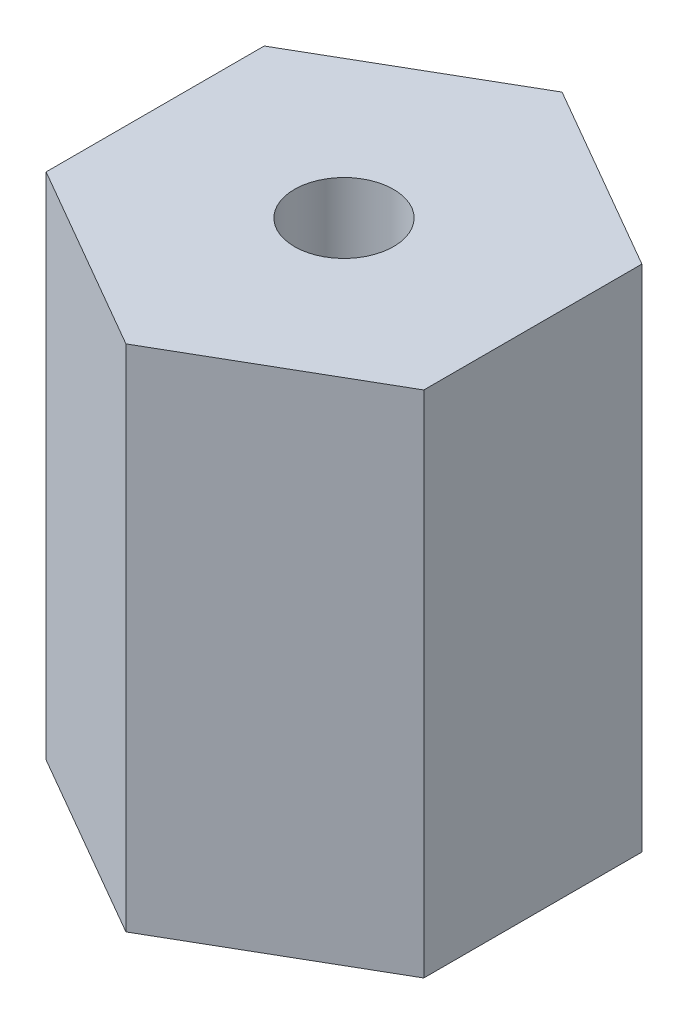
SolidWorks part; units mm, degrees
material "6061-T6 (SS)"
ref_plane "Front Plane" through (0, 0, 0) normal (0, 0, 1) x (1, 0, 0)
ref_plane "Top Plane" through (0, 0, 0) normal (0, 1, 0) x (1, 0, 0)
ref_plane "Right Plane" through (0, 0, 0) normal (1, 0, 0) x (0, 0, -1)
sketch "Sketch1" plane through (0, 0, 0) normal (0, 1, 0) x (1, 0, 0)
  line L1 (2.2606, 1.3052) -> (0, 2.6103)
  line L2 (0, 2.6103) -> (-2.2606, 1.3052)
  line L3 (-2.2606, 1.3052) -> (-2.2606, -1.3052)
  line L4 (-2.2606, -1.3052) -> (0, -2.6103)
  line L5 (0, -2.6103) -> (2.2606, -1.3052)
  line L6 (2.2606, -1.3052) -> (2.2606, 1.3052)
  circle A0 centre (0, 0) radius 2.2606 construction
  dimension "D1" = 4.5212
extrude "Boss-Extrude1" add sketch "Sketch1" along normal blind 6.096
sketch "Sketch3" plane through (0, 6.096, 0) normal (0, 1, 0) x (1, 0, 0)
  circle A0 centre (0, 0) radius 0.5937
extrude "Cut-Extrude1" cut sketch "Sketch3" against normal through all
